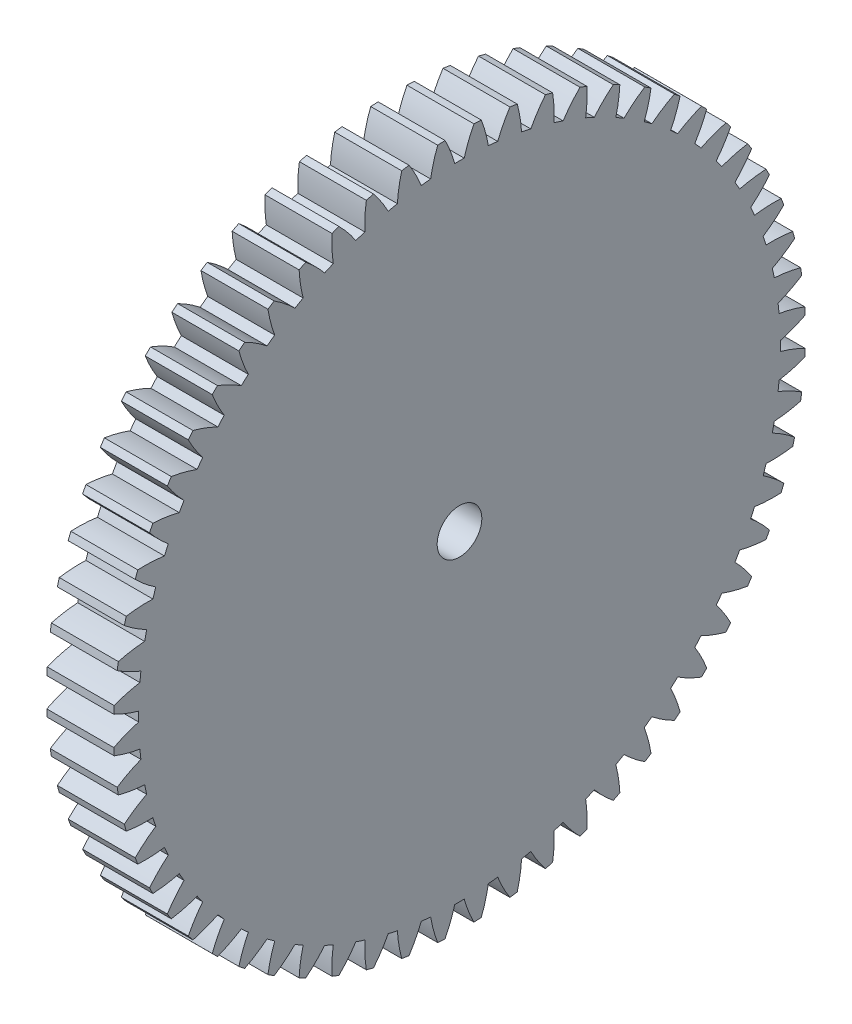
SolidWorks part; units mm, degrees
ref_plane "Plane1" through (0, 0, 0) normal (0, 0, 1) x (1, 0, 0)
ref_plane "Plane2" through (0, 0, 0) normal (0, 1, 0) x (1, 0, 0)
ref_plane "Plane3" through (0, 0, 0) normal (1, 0, 0) x (0, 0, -1)
other "Configuration Table"
sketch "HoldingSke" plane through (0, 0, 0) normal (0, 1, 0) x (1, 0, 0)
  line L0 (0, 0) -> (0.25, -0.433)
  line L1 (-15, 0) -> (100, 0) construction
  line L2 (0, 0) -> (-2.1039, 2.3779)
  line L3 (0, 0) -> (-11.863, 4.5341)
  line L4 (0, 0) -> (4.318, 7.479)
  line L5 (0, 0) -> (-46.8476, -17.4728)
  line L6 (0, 0) -> (-9.9476, -6.7116)
  line L7 (-2.1039, 2.3779) -> (8.6586, 51.2059)
  line L8 (-76.2, 54.61) -> (-74.8, 54.61)
  line L9 (-71.009, 38.7566) -> (-53.1078, 45.2721)
  line L10 (-76.2, 71.12) -> (104.1128, 71.12)
  line L11 (0, 0) -> (-12, 0)
  line L12 (-76.2, 101.6) -> (-76.133, 101.6)
  line L13 (24.9733, 27.94) -> (52.9518, 28.4284)
  line L14 (24.9733, 27.94) -> (24.9743, 27.94)
  line L15 (24.9733, 27.94) -> (100.4006, 29.5858)
  line L16 (-63.627, -2) -> (-12.827, -2)
  circle A0 centre (0, 0) radius 4
  circle A1 centre (0, 0) radius 37.5
  circle A2 centre (0, 0) radius 37.5
  circle A3 centre (0, 0) radius 4
  dimension "MHD" = 75
  dimension "Hub_dia" = 75
  dimension "Bore" = 8
  dimension "MBD" = 8
  dimension "Num_teeth" = 60
  dimension "Pitch" = 0.5
  dimension "Overall_len" = 50
  dimension "Show_teeth" = 60
  dimension "Thickness" = 12
  dimension "OAL" = 50.0001
  dimension "T_dim" = 1.4
  dimension "Ap" = 20
  dimension "H" = 19.05
  dimension "Pitch_radius" = 180.3128
  dimension "Width" = 12
  dimension "Backlash" = 0.067
  dimension "Addendum_fac" = 1
  dimension "Dedendum_fac" = 1.25
  dimension "Clearance_fac" = 0.25
  dimension "Dedendum_add" = 0.001
  dimension "Module" = 2
sketch "BasProSke" plane through (0, 0, 0) normal (0, 1, 0) x (1, 0, 0)
  line L0 (-10, 0) -> (60, 0) construction
  line L1 (0, 0) -> (0, 62)
  line L2 (0, 0) -> (12, 0)
  line L3 (12, 0) -> (12, 62)
  line L4 (12, 62) -> (0, 62)
  dimension "Thickness" = 12
  dimension "Diameter" = 124
revolve "Base-Revolve" add sketch "BasProSke" angle 360 about L0
sketch "TooCutSke" plane through (0, 0, 0) normal (1, 0, 0) x (0, 0, -1)
  line L1 (0, 0) -> (0, 107) construction
  line L2 (0, 0) -> (-1.6879, 59.9763) construction
  line L3 (0, 0) -> (-6.2785, 119.8004) construction
  line L4 (-1.6879, 59.9763) -> (-3.1392, 59.9002) construction
  arc A0 (0.8455, 57.4928) -> (-0.8455, 57.4928) centre (0, 0) ccw
  arc A1 (2.5963, 61.971) -> (-2.5963, 61.971) centre (0, 0) ccw
  circle A2 centre (0, 0) radius 60 construction
  circle A3 centre (0, 0) radius 56.3816 construction
  arc A4 (-0.8455, 57.4928) -> (-2.5963, 61.971) centre (-23.9609, 51.0368) ccw
  arc A5 (2.5963, 61.971) -> (0.8455, 57.4928) centre (23.9609, 51.0368) ccw
  dimension "Root_dia" = 114.998
  dimension "Overcut_dia" = 124.0508
  dimension "Pitch_dia" = 120
  dimension "Base_dia" = 112.7631
  dimension "Flank_rad" = 24
  dimension "Half_ang" = 3
  dimension "Half_CT" = 1.4534
extrude "ToothCut" cut sketch "TooCutSke" along normal through all
fillet "Breaks" [suppressed] radius 0.04
fillet "RootFillets" [suppressed] radius 0.501
pattern_circular "TeethCuts" count 60 every 6 about axis through (-10, 0, 0) along (1, 0, 0) of "ToothCut", "RootFillets", "Breaks"
sketch "HubNeaOneSke" plane through (0, 0, 0) normal (-1, 0, 0) x (0, 0, 1)
  circle A0 centre (0, 0) radius 37.5
  dimension "Diameter" = 75
extrude "HubNearOne" [suppressed] add sketch "HubNeaOneSke" along normal blind 38.0001
sketch "HubNeaBotSke" plane through (0, 0, 0) normal (-1, 0, 0) x (0, 0, 1)
  circle A0 centre (0, 0) radius 37.5
  dimension "Diameter" = 75
extrude "HubNearBoth" [suppressed] add sketch "HubNeaBotSke" along normal blind 19
ref_plane "FarPln" through (12, 0, 0) normal (1, 0, 0) x (0, 0, -1)
sketch "HubFarSke" plane through (12, 0, 0) normal (1, 0, 0) x (0, 0, -1)
  circle A0 centre (0, 0) radius 37.5
  dimension "Diameter" = 75
extrude "HubFar" [suppressed] add sketch "HubFarSke" along normal blind 19
sketch "BorSke" plane through (0, 0, 0) normal (1, 0, 0) x (0, 0, -1)
  circle A0 centre (0, 0) radius 4
  dimension "Diameter" = 8
extrude "Bore" cut sketch "BorSke" along normal mid plane 100.0001
sketch "KeySke" plane through (0, 0, 0) normal (1, 0, 0) x (0, 0, -1)
  line L0 (-1.5, 0) -> (-1.5, 5.4)
  line L1 (-1.5, 5.4) -> (1.5, 5.4)
  line L2 (1.5, 5.4) -> (1.5, 0)
  line L3 (0, 0) -> (0, 34) construction
  line L4 (-1.5, 0) -> (1.5, 0)
  dimension "Offset" = 5.4
  dimension "Width" = 3
extrude "Keyway" [suppressed] cut sketch "KeySke" along normal mid plane 100.0001
pattern_circular "Keyway2" [suppressed] count 2 every 90 about axis through (-10, 0, 0) along (1, 0, 0)
equation "' \"Module@HoldingSke\" = 6.35"
equation "' \"Num_teeth@HoldingSke\" = 12"
equation "' \"Ap@HoldingSke\" =  20"
equation "' \"Ap@HoldingSke\" = 20"
equation "' \"Width@HoldingSke\" = 0.5 * 25.4"
equation "' \"Hub_dia@HoldingSke\"= 1 * 25.4"
equation "' \"Hub_dia@HoldingSke\" = 1 * 25.4"
equation "' \"Overall_len@HoldingSke\" = 1.0 * 25.4"
equation "' \"Bore@HoldingSke\" = 0.75 * 25.4"
equation "' \"T_dim@HoldingSke\" = 0.1 * 25.4"
equation "' \"Width@KeySke\" = 0.25 * 25.4"
equation "' \"Show_teeth@HoldingSke\" = 13"
equation "' \"Backlash@HoldingSke\" = 0.009 * 25.4"
equation "' \"Addendum_fac@HoldingSke\" = 1.0"
equation "' \"Dedendum_fac@HoldingSke\" = 1.25"
equation "' \"Dedendum_add@HoldingSke\" = 0.00005 * 25.4"
equation "' \"Clearance_fac@HoldingSke\" = 0.25"
equation "\"Pitch@HoldingSke\" = 1 / \"Module@HoldingSke\""
equation "\"Overcut_dia@TooCutSke\" = (\"Num_teeth@HoldingSke\" + 2 * \"Addendum_fac@HoldingSke\") / \"Pitch@HoldingSke\" + 0.002 * 25.4"
equation "\"Pitch_dia@TooCutSke\" = \"Num_teeth@HoldingSke\" / \"Pitch@HoldingSke\""
equation "\"Base_dia@TooCutSke\" = \"Num_teeth@HoldingSke\" / \"Pitch@HoldingSke\" * cos((\"Ap@HoldingSke\"  * 3.14159265 / 180))"
equation "\"Root_dia@TooCutSke\" = (\"Num_teeth@HoldingSke\" + 2) / \"Pitch@HoldingSke\" - 2 * (\"Addendum_fac@HoldingSke\" + \"Dedendum_fac@HoldingSke\") / \"Pitch@HoldingSke\" - \"Dedendum_add@HoldingSke\" * 2"
equation "\"Half_ang@TooCutSke\" = 180 / \"Num_teeth@HoldingSke\""
equation "\"Half_CT@TooCutSke\" = \"Num_teeth@HoldingSke\" / \"Pitch@HoldingSke\" * sin((3.14159265 / 2 / \"Num_teeth@HoldingSke\")) / 2 - 7 * \"Backlash@HoldingSke\" / 4"
equation "\"Flank_rad@TooCutSke\" = \"Num_teeth@HoldingSke\" / \"Pitch@HoldingSke\" / 5"
equation "\"Radius@RootFillets\" = \"Clearance_fac@HoldingSke\" / \"Pitch@HoldingSke\" + \"Dedendum_add@HoldingSke\""
equation "\"Break_rad@Breaks\" = 0.02 / \"Pitch@HoldingSke\""
equation "\"Thickness@HoldingSke\" = \"Width@HoldingSke\""
equation "\"OAL@HoldingSke\" = \"Thickness@HoldingSke\""
equation "\"MHD@HoldingSke\" = (\"Num_teeth@HoldingSke\" + 2) / \"Pitch@HoldingSke\" - 2 * (\"Addendum_fac@HoldingSke\" + \"Dedendum_fac@HoldingSke\")  / \"Pitch@HoldingSke\" - \"Dedendum_add@HoldingSke\" * 2"
equation "\"MBD@HoldingSke\" = (\"Num_teeth@HoldingSke\" + 2) / \"Pitch@HoldingSke\" - 2 * (\"Addendum_fac@HoldingSke\" + \"Dedendum_fac@HoldingSke\")  / \"Pitch@HoldingSke\" - \"Dedendum_add@HoldingSke\" * 2 - 0.002 * 25.4"
equation "\"MHD@HoldingSke\" = ((sgn( \"MHD@HoldingSke\" - \"Hub_dia@HoldingSke\" )-1)*( \"MHD@HoldingSke\" - \"Hub_dia@HoldingSke\" ))/-2+ \"Hub_dia@HoldingSke\""
equation "\"MBD@HoldingSke\" = ((sgn( \"MBD@HoldingSke\" - \"Bore@HoldingSke\" )-1)*( \"MBD@HoldingSke\" - \"Bore@HoldingSke\" ))/-2+ \"Bore@HoldingSke\""
equation "\"OAL@HoldingSke\" = ((sgn( \"OAL@HoldingSke\" - \"Overall_len@HoldingSke\" )+1)*( \"OAL@HoldingSke\" - \"Overall_len@HoldingSke\" ))/2 + \"Overall_len@HoldingSke\" + 0.000002 * 25.4"
equation "\"Num_teeth@TeethCuts\" = int( \"Show_teeth@HoldingSke\" ) + 1"
equation "\"Num_teeth@TeethCuts\" = ((sgn( \"Num_teeth@TeethCuts\" - \"Num_teeth@HoldingSke\" )-1)*( \"Num_teeth@TeethCuts\" - \"Num_teeth@HoldingSke\" ))/-2+ \"Num_teeth@HoldingSke\""
equation "\"Num_teeth@TeethCuts\" = ((sgn( \"Num_teeth@TeethCuts\" - 2.0)+1)*( \"Num_teeth@TeethCuts\" - 2.0))/2 +2.0"
equation "\"Angle@TeethCuts\" = 360.0 / \"Num_teeth@HoldingSke\""
equation "\"Diameter@BasProSke\" = (\"Num_teeth@HoldingSke\" + 2 * \"Addendum_fac@HoldingSke\") / \"Pitch@HoldingSke\""
equation "\"Thickness@BasProSke\"  = \"Thickness@HoldingSke\""
equation "' \"Fillet_rad@BasProSke\" =  \"Thickness@HoldingSke\" * 0.05"
equation "' \"Fillet_rad@BasProSke\" = \"Thickness@HoldingSke\" * 0.05"
equation "\"MHD@HoldingSke\" = ((sgn( \"MHD@HoldingSke\" - \"Root_dia@TooCutSke\" )-1)*( \"MHD@HoldingSke\" - \"Root_dia@TooCutSke\" ))/-2+ \"Root_dia@TooCutSke\""
equation "\"Diameter@HubNeaOneSke\" = \"MHD@HoldingSke\""
equation "\"Length@HubNearOne\" = \"OAL@HoldingSke\" - \"Thickness@BasProSke\""
equation "\"Diameter@HubNeaBotSke\" = \"MHD@HoldingSke\""
equation "\"Length@HubNearBoth\" = ( \"OAL@HoldingSke\" - \"Thickness@BasProSke\" ) / 2.0"
equation "\"Thickness@FarPln\" = \"Thickness@BasProSke\""
equation "\"Diameter@HubFarSke\" = \"MHD@HoldingSke\""
equation "\"Length@HubFar\" = ( \"OAL@HoldingSke\" - \"Thickness@BasProSke\" ) / 2.0"
equation "\"Diameter@BorSke\" = \"MBD@HoldingSke\""
equation "\"D1@Bore\" = \"OAL@HoldingSke\" * 2.0"
equation "\"D1@Keyway\" = \"OAL@HoldingSke\" * 2.0"
equation "\"Offset@KeySke\" = \"T_dim@HoldingSke\" + \"MBD@HoldingSke\" / 2.0"
